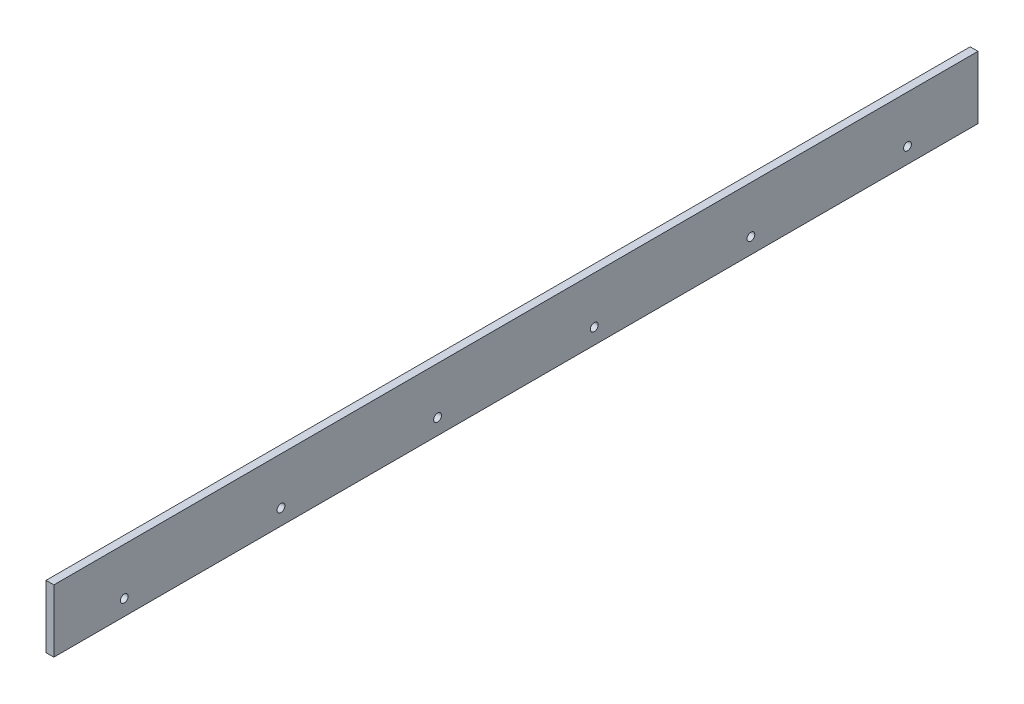
SolidWorks part; units mm, degrees
material "1060 合金"
ref_plane "前视基准面" through (0, 0, 0) normal (0, 0, 1) x (1, 0, 0)
ref_plane "上视基准面" through (0, 0, 0) normal (0, 1, 0) x (1, 0, 0)
ref_plane "右视基准面" through (0, 0, 0) normal (1, 0, 0) x (0, 0, -1)
other "Configuration Table"
sketch "草图1" plane through (0, 0, 0) normal (0, 0, 1) x (1, 0, 0)
  line L1 (-2.5, 20) -> (2.5, 20)
  line L2 (-2.5, 20) -> (-2.5, -20)
  line L3 (-2.5, -20) -> (2.5, -20)
  line L4 (2.5, 20) -> (2.5, -20)
  line L5 (-2.5, 20) -> (2.5, -20) construction
  line L6 (-2.5, -20) -> (2.5, 20) construction
  point P0 (0, 0)
  dimension "D1" = 5
  dimension "D2" = 40
extrude "凸台-拉伸1" add sketch "草图1" along normal blind 590
sketch "草图2" plane through (2.5, 0, 0) normal (1, 0, 0) x (0, 0, -1)
  line L0 (-590, -10) -> (0, -10) construction
  line L1 (-295, 20) -> (-295, -20) construction
  line L2 (-590, 20) -> (0, 20) construction
  line L4 (-590, 20) -> (-590, -20)
  line L5 (0, 20) -> (-590, 20)
  line L6 (0, -20) -> (0, 20)
  line L7 (0, 20) -> (-590, 20)
  line L8 (-590, 20) -> (-590, -20)
  line L10 (0, -20) -> (0, 20)
  line L14 (-590, -20) -> (0, -20)
  line L15 (-590, -20) -> (0, -20)
  circle A0 centre (-345, -10) radius 2.5
  circle A1 centre (-445, -10) radius 2.5
  circle A2 centre (-145, -10) radius 2.5
  circle A3 centre (-245, -10) radius 2.5
  circle A4 centre (-545, -10) radius 2.5
  circle A5 centre (-45, -10) radius 2.5
  dimension "D3" = 5
  dimension "D4" = 5
  dimension "D5" = 100
  dimension "D6" = 100
  dimension "D7" = 5
  dimension "D8" = 100
  dimension "D2" = 20
  dimension "D1" = 0
extrude "切除-拉伸1" cut sketch "草图2" against normal through all contours A4 | A1 | A0 | A3 | A2 | A5
